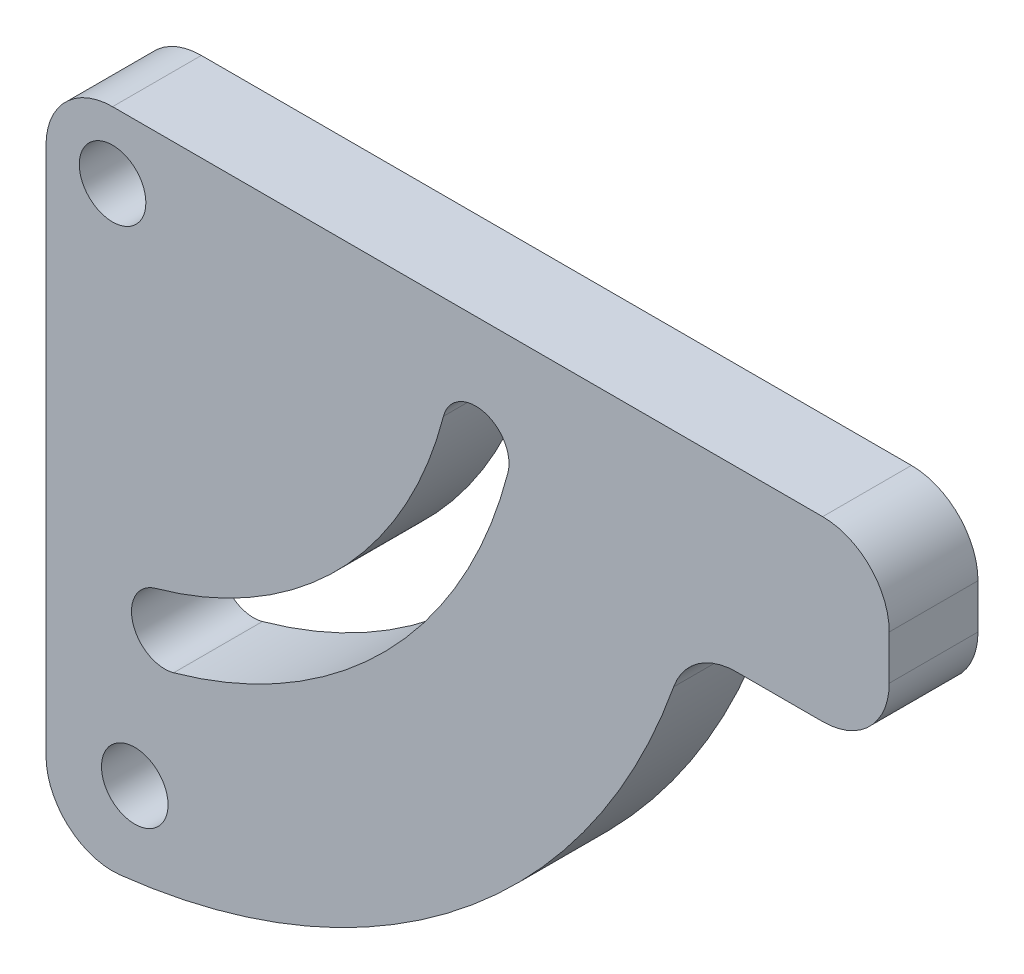
SolidWorks part; units mm, degrees
ref_plane "Front Plane" through (0, 0, 0) normal (0, 0, 1) x (1, 0, 0)
ref_plane "Top Plane" through (0, 0, 0) normal (0, 1, 0) x (1, 0, 0)
ref_plane "Right Plane" through (0, 0, 0) normal (1, 0, 0) x (0, 0, -1)
sketch "Sketch1" plane through (0, 0, 0) normal (0, 0, 1) x (1, 0, 0)
  line L0 (0, 0) -> (30, 0)
  line L1 (0, 0) -> (0, -30)
  line L2 (28.9137, -8) -> (38, -8)
  line L3 (38, -8) -> (38, 0)
  line L4 (38, 0) -> (30, 0)
  arc A0 (0, -30) -> (28.9137, -8) centre (0, 0) ccw
  circle A1 centre (4, -26) radius 1.5
  arc A2 (4.9509, -17.8252) -> (5.7538, -20.7158) centre (5.3523, -19.2705) ccw
  arc A3 (20.8173, -5.375) -> (17.9125, -4.625) centre (19.3649, -5) ccw
  arc A4 (5.3523, -19.2705) -> (19.3649, -5) centre (0, 0) ccw construction
  arc A5 (4.9509, -17.8252) -> (17.9125, -4.625) centre (0, 0) ccw
  arc A6 (5.7538, -20.7158) -> (20.8173, -5.375) centre (0, 0) ccw
  circle A7 centre (3, -3) radius 1.5
  point P17 (0, 0)
  point P19 (2.2246, 0)
  point P20 (0.8832, -42.3346)
  dimension "D2" = 3
  dimension "D3" = 3
  dimension "D8" = 30
  dimension "D12" = 20
  dimension "D1" = 20
  dimension "D4" = 3
  dimension "D5" = 3
  dimension "D6" = 4
  dimension "D7" = 4
  dimension "D9" = 8
  dimension "D10" = 8
  dimension "D11" = 5
extrude "Boss-Extrude1" add sketch "Sketch1" along normal blind 4
fillet "Fillet1" radius 3 5 edges at (0, -30, 2) (38, -8, 2) (28.9137, -8, 2) (38, 0, 2) (0, 0, 2)
